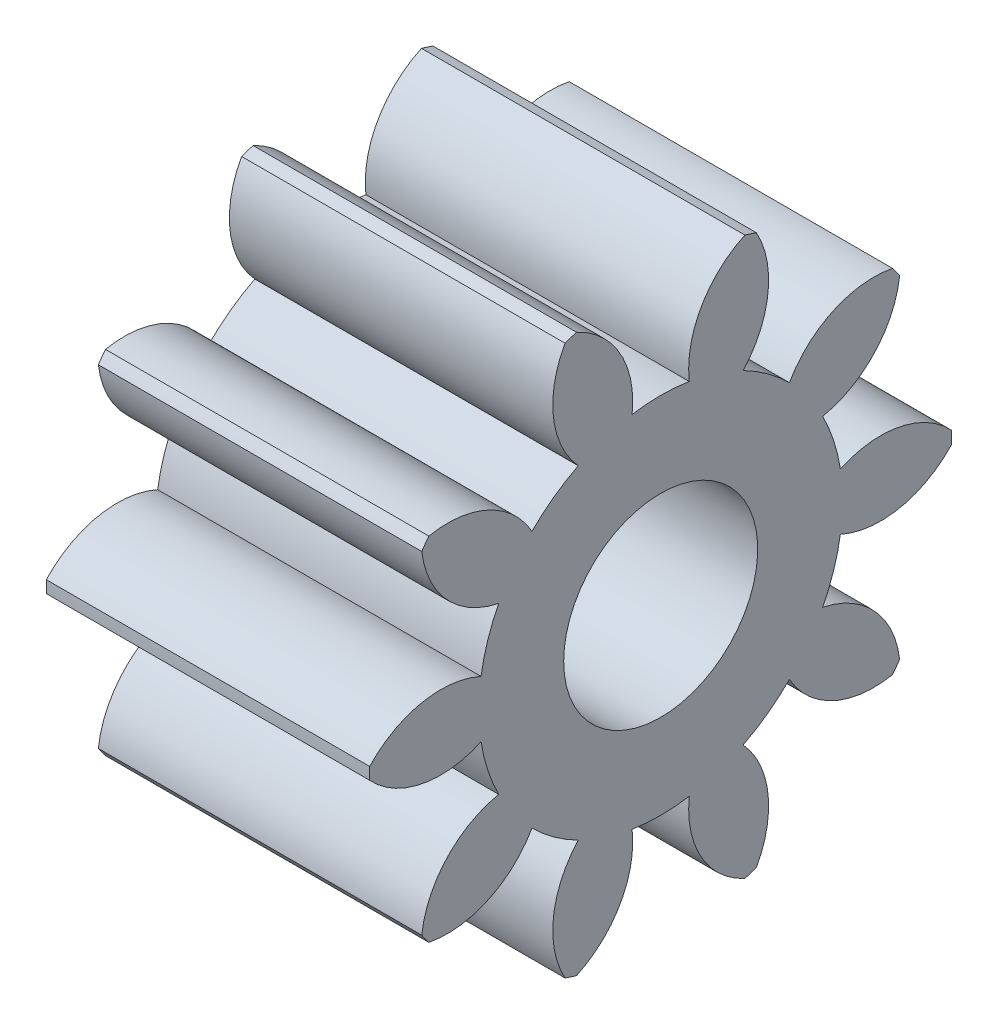
SolidWorks part; units mm, degrees
ref_plane "Plane1" through (0, 0, 0) normal (0, 0, 1) x (1, 0, 0)
ref_plane "Plane2" through (0, 0, 0) normal (0, 1, 0) x (1, 0, 0)
ref_plane "Plane3" through (0, 0, 0) normal (1, 0, 0) x (0, 0, -1)
sketch "HoldingSke" plane through (0, 0, 0) normal (0, 1, 0) x (1, 0, 0)
  line L0 (0, 0) -> (0.6565, -0.1158)
  line L1 (-15, 0) -> (100, 0) construction
  line L2 (0, 0) -> (-2.1039, 2.3779)
  line L3 (0, 0) -> (-11.863, 4.5341)
  line L4 (0, 0) -> (8.5048, 1.4996)
  line L5 (0, 0) -> (-46.8476, -17.4728)
  line L6 (0, 0) -> (-8.2896, -5.593)
  line L7 (-2.1039, 2.3779) -> (8.6586, 51.2059)
  line L8 (-76.2, 54.61) -> (-75.2, 54.61)
  line L9 (-71.009, 38.7566) -> (-53.1078, 45.2721)
  line L10 (-76.2, 71.12) -> (104.1128, 71.12)
  line L11 (0, 0) -> (-10, 0)
  line L12 (-76.2, 101.6) -> (-76.147, 101.6)
  line L13 (24.9733, 27.94) -> (52.9518, 28.4284)
  line L14 (24.9733, 27.94) -> (24.9743, 27.94)
  line L15 (24.9733, 27.94) -> (100.4006, 29.5858)
  line L16 (-63.627, -1.5) -> (-12.827, -1.5)
  circle A0 centre (0, 0) radius 3
  circle A1 centre (0, 0) radius 5.624
  circle A2 centre (0, 0) radius 37.5
  circle A3 centre (0, 0) radius 3
  dimension "MHD" = 11.248
  dimension "Hub_dia" = 75
  dimension "Bore" = 6
  dimension "MBD" = 6
  dimension "Num_teeth" = 10
  dimension "Pitch" = 0.6667
  dimension "Overall_len" = 50
  dimension "Show_teeth" = 10
  dimension "Thickness" = 10
  dimension "OAL" = 50.0001
  dimension "T_dim" = 1
  dimension "Ap" = 20
  dimension "H" = 19.05
  dimension "Pitch_radius" = 180.3128
  dimension "Width" = 10
  dimension "Backlash" = 0.053
  dimension "Addendum_fac" = 1
  dimension "Dedendum_fac" = 1.25
  dimension "Clearance_fac" = 0.25
  dimension "Dedendum_add" = 0.001
  dimension "Module" = 1.5
sketch "BasProSke" plane through (0, 0, 0) normal (0, 1, 0) x (1, 0, 0)
  line L0 (-10, 0) -> (60, 0) construction
  line L1 (0, 0) -> (0, 9)
  line L2 (0, 0) -> (10, 0)
  line L3 (10, 0) -> (10, 9)
  line L4 (10, 9) -> (0, 9)
  dimension "Thickness" = 10
  dimension "Diameter" = 18
revolve "Base-Revolve" add sketch "BasProSke" angle 360 about L0
sketch "TooCutSke" plane through (0, 0, 0) normal (1, 0, 0) x (0, 0, -1)
  line L1 (0, 0) -> (0, 107) construction
  line L2 (0, 0) -> (-1.2658, 7.3924) construction
  line L3 (0, 0) -> (-4.5869, 14.117) construction
  line L4 (-1.2658, 7.3924) -> (-2.2934, 7.0585) construction
  arc A0 (0.8839, 5.5541) -> (-0.8839, 5.5541) centre (0, 0) ccw
  arc A1 (2.6378, 8.6313) -> (-2.6378, 8.6313) centre (0, 0) ccw
  circle A2 centre (0, 0) radius 7.5 construction
  circle A3 centre (0, 0) radius 7.0477 construction
  arc A4 (-0.8839, 5.5541) -> (-2.6378, 8.6313) centre (-3.8646, 5.8936) ccw
  arc A5 (2.6378, 8.6313) -> (0.8839, 5.5541) centre (3.8646, 5.8936) ccw
  dimension "Root_dia" = 11.248
  dimension "Overcut_dia" = 18.0508
  dimension "Pitch_dia" = 15
  dimension "Base_dia" = 14.0954
  dimension "Flank_rad" = 3
  dimension "Half_ang" = 18
  dimension "Half_CT" = 1.0805
extrude "ToothCut" cut sketch "TooCutSke" along normal through all
fillet "Breaks" [suppressed] radius 0.03
fillet "RootFillets" [suppressed] radius 0.376
pattern_circular "TeethCuts" count 10 every 36 about axis through (-10, 0, 0) along (1, 0, 0) of "ToothCut", "RootFillets", "Breaks"
sketch "HubNeaOneSke" plane through (0, 0, 0) normal (-1, 0, 0) x (0, 0, 1)
  circle A0 centre (0, 0) radius 5.624
  dimension "Diameter" = 11.248
extrude "HubNearOne" [suppressed] add sketch "HubNeaOneSke" along normal blind 40.0001
sketch "HubNeaBotSke" plane through (0, 0, 0) normal (-1, 0, 0) x (0, 0, 1)
  circle A0 centre (0, 0) radius 5.624
  dimension "Diameter" = 11.248
extrude "HubNearBoth" [suppressed] add sketch "HubNeaBotSke" along normal blind 20
ref_plane "FarPln" through (10, 0, 0) normal (1, 0, 0) x (0, 0, -1)
sketch "HubFarSke" plane through (10, 0, 0) normal (1, 0, 0) x (0, 0, -1)
  circle A0 centre (0, 0) radius 5.624
  dimension "Diameter" = 11.248
extrude "HubFar" [suppressed] add sketch "HubFarSke" along normal blind 20
sketch "BorSke" plane through (0, 0, 0) normal (1, 0, 0) x (0, 0, -1)
  circle A0 centre (0, 0) radius 3
  dimension "Diameter" = 6
extrude "Bore" cut sketch "BorSke" along normal mid plane 100.0001
sketch "KeySke" plane through (0, 0, 0) normal (1, 0, 0) x (0, 0, -1)
  line L0 (-1, 0) -> (-1, 4)
  line L1 (-1, 4) -> (1, 4)
  line L2 (1, 4) -> (1, 0)
  line L3 (0, 0) -> (0, 34) construction
  line L4 (-1, 0) -> (1, 0)
  dimension "Offset" = 4
  dimension "Width" = 2
extrude "Keyway" [suppressed] cut sketch "KeySke" along normal mid plane 100.0001
pattern_circular "Keyway2" [suppressed] count 2 every 90 about axis through (-10, 0, 0) along (1, 0, 0)
equation "' \"Module@HoldingSke\" = 6.35"
equation "' \"Num_teeth@HoldingSke\" = 12"
equation "' \"Ap@HoldingSke\" =  20"
equation "' \"Ap@HoldingSke\" = 20"
equation "' \"Width@HoldingSke\" = 0.5 * 25.4"
equation "' \"Hub_dia@HoldingSke\"= 1 * 25.4"
equation "' \"Hub_dia@HoldingSke\" = 1 * 25.4"
equation "' \"Overall_len@HoldingSke\" = 1.0 * 25.4"
equation "' \"Bore@HoldingSke\" = 0.75 * 25.4"
equation "' \"T_dim@HoldingSke\" = 0.1 * 25.4"
equation "' \"Width@KeySke\" = 0.25 * 25.4"
equation "' \"Show_teeth@HoldingSke\" = 13"
equation "' \"Backlash@HoldingSke\" = 0.009 * 25.4"
equation "' \"Addendum_fac@HoldingSke\" = 1.0"
equation "' \"Dedendum_fac@HoldingSke\" = 1.25"
equation "' \"Dedendum_add@HoldingSke\" = 0.00005 * 25.4"
equation "' \"Clearance_fac@HoldingSke\" = 0.25"
equation "\"Pitch@HoldingSke\" = 1 / \"Module@HoldingSke\""
equation "\"Overcut_dia@TooCutSke\" = (\"Num_teeth@HoldingSke\" + 2 * \"Addendum_fac@HoldingSke\") / \"Pitch@HoldingSke\" + 0.002 * 25.4"
equation "\"Pitch_dia@TooCutSke\" = \"Num_teeth@HoldingSke\" / \"Pitch@HoldingSke\""
equation "\"Base_dia@TooCutSke\" = \"Num_teeth@HoldingSke\" / \"Pitch@HoldingSke\" * cos((\"Ap@HoldingSke\"  * 3.14159265 / 180))"
equation "\"Root_dia@TooCutSke\" = (\"Num_teeth@HoldingSke\" + 2) / \"Pitch@HoldingSke\" - 2 * (\"Addendum_fac@HoldingSke\" + \"Dedendum_fac@HoldingSke\") / \"Pitch@HoldingSke\" - \"Dedendum_add@HoldingSke\" * 2"
equation "\"Half_ang@TooCutSke\" = 180 / \"Num_teeth@HoldingSke\""
equation "\"Half_CT@TooCutSke\" = \"Num_teeth@HoldingSke\" / \"Pitch@HoldingSke\" * sin((3.14159265 / 2 / \"Num_teeth@HoldingSke\")) / 2 - 7 * \"Backlash@HoldingSke\" / 4"
equation "\"Flank_rad@TooCutSke\" = \"Num_teeth@HoldingSke\" / \"Pitch@HoldingSke\" / 5"
equation "\"Radius@RootFillets\" = \"Clearance_fac@HoldingSke\" / \"Pitch@HoldingSke\" + \"Dedendum_add@HoldingSke\""
equation "\"Break_rad@Breaks\" = 0.02 / \"Pitch@HoldingSke\""
equation "\"Thickness@HoldingSke\" = \"Width@HoldingSke\""
equation "\"OAL@HoldingSke\" = \"Thickness@HoldingSke\""
equation "\"MHD@HoldingSke\" = (\"Num_teeth@HoldingSke\" + 2) / \"Pitch@HoldingSke\" - 2 * (\"Addendum_fac@HoldingSke\" + \"Dedendum_fac@HoldingSke\")  / \"Pitch@HoldingSke\" - \"Dedendum_add@HoldingSke\" * 2"
equation "\"MBD@HoldingSke\" = (\"Num_teeth@HoldingSke\" + 2) / \"Pitch@HoldingSke\" - 2 * (\"Addendum_fac@HoldingSke\" + \"Dedendum_fac@HoldingSke\")  / \"Pitch@HoldingSke\" - \"Dedendum_add@HoldingSke\" * 2 - 0.002 * 25.4"
equation "\"MHD@HoldingSke\" = ((sgn( \"MHD@HoldingSke\" - \"Hub_dia@HoldingSke\" )-1)*( \"MHD@HoldingSke\" - \"Hub_dia@HoldingSke\" ))/-2+ \"Hub_dia@HoldingSke\""
equation "\"MBD@HoldingSke\" = ((sgn( \"MBD@HoldingSke\" - \"Bore@HoldingSke\" )-1)*( \"MBD@HoldingSke\" - \"Bore@HoldingSke\" ))/-2+ \"Bore@HoldingSke\""
equation "\"OAL@HoldingSke\" = ((sgn( \"OAL@HoldingSke\" - \"Overall_len@HoldingSke\" )+1)*( \"OAL@HoldingSke\" - \"Overall_len@HoldingSke\" ))/2 + \"Overall_len@HoldingSke\" + 0.000002 * 25.4"
equation "\"Num_teeth@TeethCuts\" = int( \"Show_teeth@HoldingSke\" ) + 1"
equation "\"Num_teeth@TeethCuts\" = ((sgn( \"Num_teeth@TeethCuts\" - \"Num_teeth@HoldingSke\" )-1)*( \"Num_teeth@TeethCuts\" - \"Num_teeth@HoldingSke\" ))/-2+ \"Num_teeth@HoldingSke\""
equation "\"Num_teeth@TeethCuts\" = ((sgn( \"Num_teeth@TeethCuts\" - 2.0)+1)*( \"Num_teeth@TeethCuts\" - 2.0))/2 +2.0"
equation "\"Angle@TeethCuts\" = 360.0 / \"Num_teeth@HoldingSke\""
equation "\"Diameter@BasProSke\" = (\"Num_teeth@HoldingSke\" + 2 * \"Addendum_fac@HoldingSke\") / \"Pitch@HoldingSke\""
equation "\"Thickness@BasProSke\"  = \"Thickness@HoldingSke\""
equation "' \"Fillet_rad@BasProSke\" =  \"Thickness@HoldingSke\" * 0.05"
equation "' \"Fillet_rad@BasProSke\" = \"Thickness@HoldingSke\" * 0.05"
equation "\"MHD@HoldingSke\" = ((sgn( \"MHD@HoldingSke\" - \"Root_dia@TooCutSke\" )-1)*( \"MHD@HoldingSke\" - \"Root_dia@TooCutSke\" ))/-2+ \"Root_dia@TooCutSke\""
equation "\"Diameter@HubNeaOneSke\" = \"MHD@HoldingSke\""
equation "\"Length@HubNearOne\" = \"OAL@HoldingSke\" - \"Thickness@BasProSke\""
equation "\"Diameter@HubNeaBotSke\" = \"MHD@HoldingSke\""
equation "\"Length@HubNearBoth\" = ( \"OAL@HoldingSke\" - \"Thickness@BasProSke\" ) / 2.0"
equation "\"Thickness@FarPln\" = \"Thickness@BasProSke\""
equation "\"Diameter@HubFarSke\" = \"MHD@HoldingSke\""
equation "\"Length@HubFar\" = ( \"OAL@HoldingSke\" - \"Thickness@BasProSke\" ) / 2.0"
equation "\"Diameter@BorSke\" = \"MBD@HoldingSke\""
equation "\"D1@Bore\" = \"OAL@HoldingSke\" * 2.0"
equation "\"D1@Keyway\" = \"OAL@HoldingSke\" * 2.0"
equation "\"Offset@KeySke\" = \"T_dim@HoldingSke\" + \"MBD@HoldingSke\" / 2.0"
